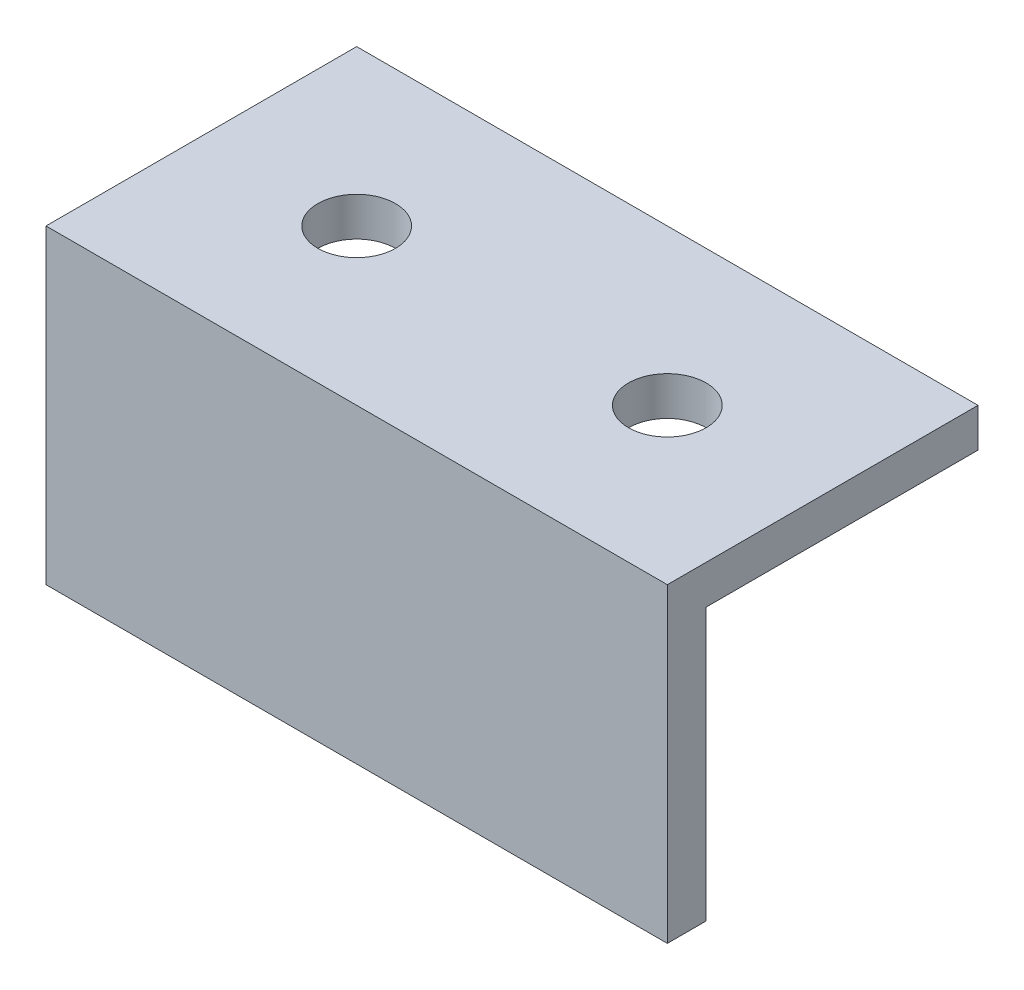
SolidWorks part; units mm, degrees
material "6061 Alloy"
ref_plane "Front Plane" through (0, 0, 0) normal (0, 0, 1) x (1, 0, 0)
ref_plane "Top Plane" through (0, 0, 0) normal (0, 1, 0) x (1, 0, 0)
ref_plane "Right Plane" through (0, 0, 0) normal (1, 0, 0) x (0, 0, -1)
sketch "Sketch1" plane through (0, 0, 0) normal (1, 0, 0) x (0, 0, -1)
  line L0 (0, 0) -> (0, 12.7)
  line L1 (0, 12.7) -> (12.7, 12.7)
  line L2 (12.7, 12.7) -> (12.7, 11.1125)
  line L3 (12.7, 11.1125) -> (1.5875, 11.1125)
  line L4 (1.5875, 11.1125) -> (1.5875, 0)
  line L5 (1.5875, 0) -> (0, 0)
  dimension "width" = 12.7
  dimension "thickness" = 1.5875
extrude "Extrude1" add sketch "Sketch1" along normal blind 25.4
sketch "Sketch2" plane through (0, 12.7, 0) normal (0, 1, 0) x (1, 0, 0)
  line L0 (0, 12.7) -> (0, 0) construction
  line L1 (25.4, 0) -> (0, 0) construction
  circle A0 centre (19.05, 6.35) radius 1.5875
  circle A1 centre (6.35, 6.35) radius 1.5875
  dimension "D1" = 12.7
  dimension "hole_dia" = 3.175
  dimension "D2" = 6.35
  dimension "D3" = 6.35
  dimension "D4" = 6.35
extrude "Extrude2" cut sketch "Sketch2" against normal up to surface (20.6866 mm away)
equation "\"D3@Sketch2\" = \"width\"/2"
equation "\"D4@Sketch2\" = \"width\"/2"
